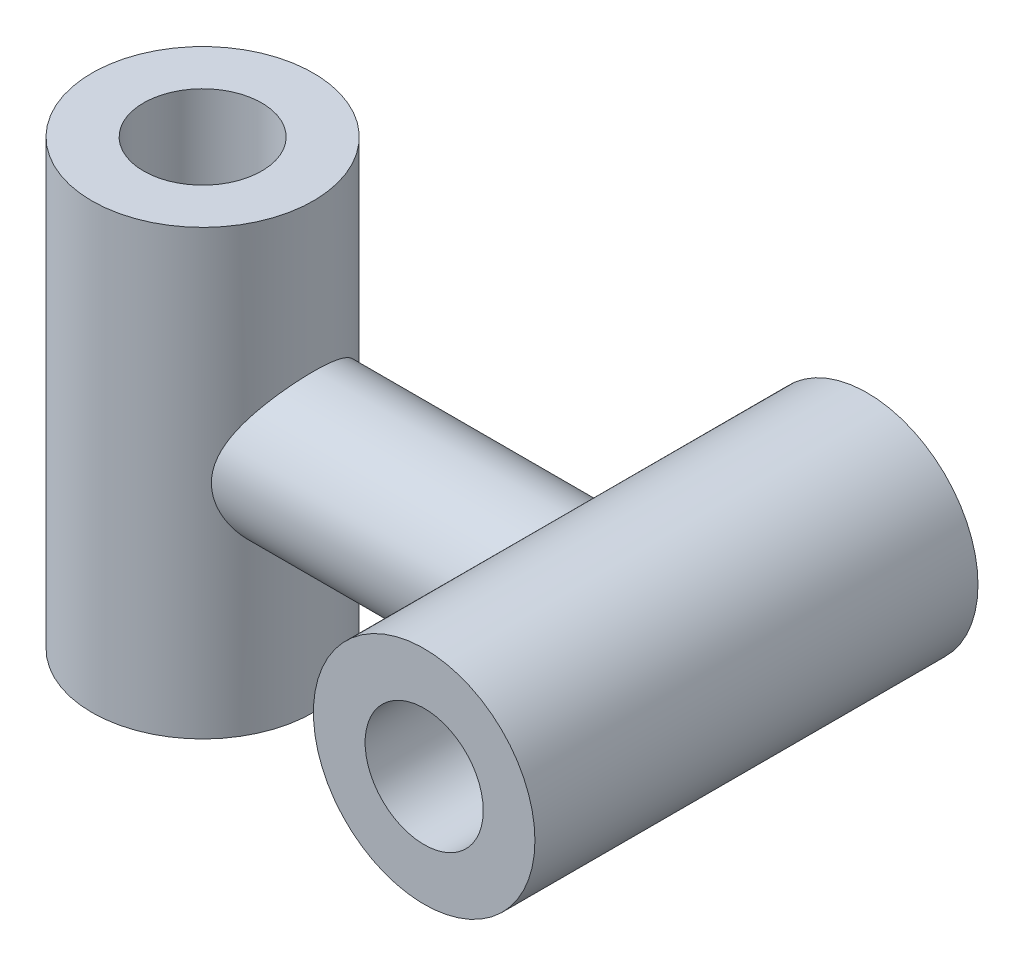
SolidWorks part; units mm, degrees
material "Alloy Steel"
ref_plane "Front" through (0, 0, 0) normal (0, 0, 1) x (1, 0, 0)
ref_plane "Top" through (0, 0, 0) normal (0, 1, 0) x (1, 0, 0)
ref_plane "Right" through (0, 0, 0) normal (1, 0, 0) x (0, 0, -1)
sketch "Sketch1" plane through (0, 0, 0) normal (0, 1, 0) x (1, 0, 0)
  circle A0 centre (0, 0) radius 8
  circle A1 centre (0, 0) radius 15
  dimension "D1" = 30
  dimension "D2" = 16
extrude "Boss-Extrude1" add sketch "Sketch1" along normal mid plane 60
sketch "Sketch3" plane through (0, 0, 0) normal (0, 0, 1) x (1, 0, 0)
  line L0 (-4.0547, 0) -> (39.4848, 0) construction
  line L1 (60, 9.2196) -> (60, -8.3507) construction
  circle A0 centre (60, 0) radius 8
  circle A1 centre (60, 0) radius 15
  dimension "D2" = 30
  dimension "D3" = 16
  dimension "D1" = 60
extrude "Boss-Extrude3" add sketch "Sketch3" along normal mid plane 60
ref_plane "Plane1" through (15, 0, 0) normal (1, 0, 0) x (0, 0, -1)
sketch "Sketch4" plane through (15, 0, 0) normal (1, 0, 0) x (0, 0, -1)
  circle A0 centre (0, 0) radius 10
  dimension "D1" = 20
extrude "Boss-Extrude4" add sketch "Sketch4" along normal up to next and the other way up to next
